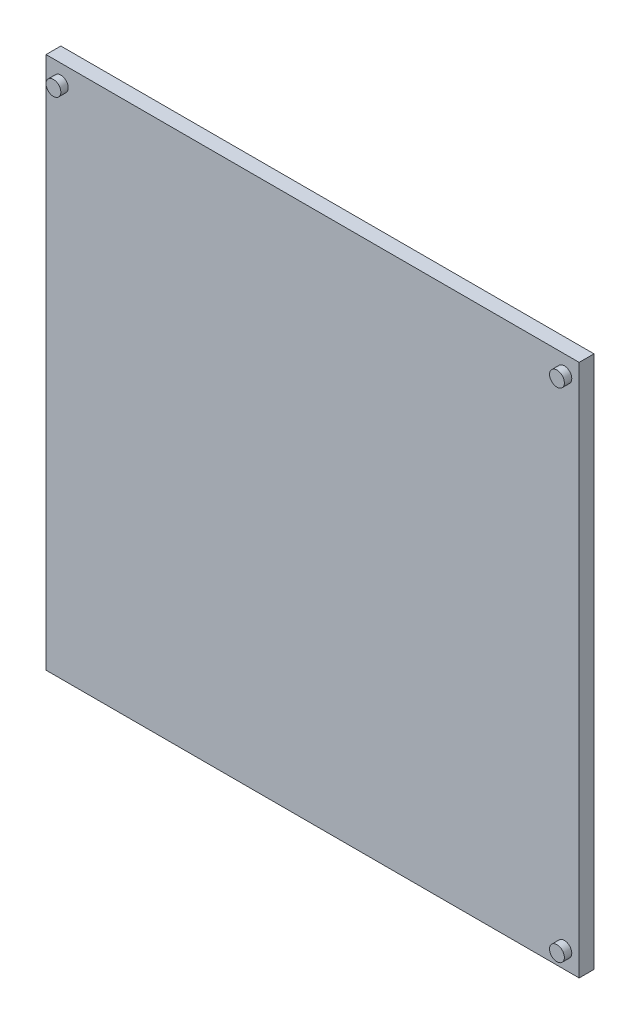
SolidWorks part; units mm, degrees
ref_plane "Front Plane" through (0, 0, 0) normal (0, 0, 1) x (1, 0, 0)
ref_plane "Top Plane" through (0, 0, 0) normal (0, 1, 0) x (1, 0, 0)
ref_plane "Right Plane" through (0, 0, 0) normal (1, 0, 0) x (0, 0, -1)
sketch "Sketch1" plane through (0, 0, 0) normal (0, 0, 1) x (1, 0, 0)
  line L1 (-45, -45) -> (45, -45)
  line L2 (-45, -45) -> (-45, 45)
  line L3 (-45, 45) -> (45, 45)
  line L4 (45, -45) -> (45, 45)
  line L5 (-45, -45) -> (45, 45) construction
  line L6 (-45, 45) -> (45, -45) construction
  point P0 (0, 0)
  dimension "D1" = 90
  dimension "D2" = 90
extrude "Boss-Extrude1" add sketch "Sketch1" along normal blind 2.5
sketch "Sketch2" plane through (0, 0, 2.5) normal (0, 0, 1) x (1, 0, 0)
  line L0 (0, 45) -> (0, -45) construction
  line L1 (45, 45) -> (-45, 45) construction
  line L2 (-45, -45) -> (45, -45) construction
  line L3 (-45, 0) -> (45, 0) construction
  line L4 (-45, 45) -> (-45, -45) construction
  line L5 (45, -45) -> (45, 45) construction
  circle A0 centre (-42.5, 42) radius 1.25
  circle A1 centre (42.5, 42) radius 1.25
  circle A2 centre (42.5, -42) radius 1.25
  dimension "D1" = 2.5
  dimension "D2" = 3
  dimension "D3" = 2.5
extrude "Boss-Extrude2" add sketch "Sketch2" along normal blind 1.25
